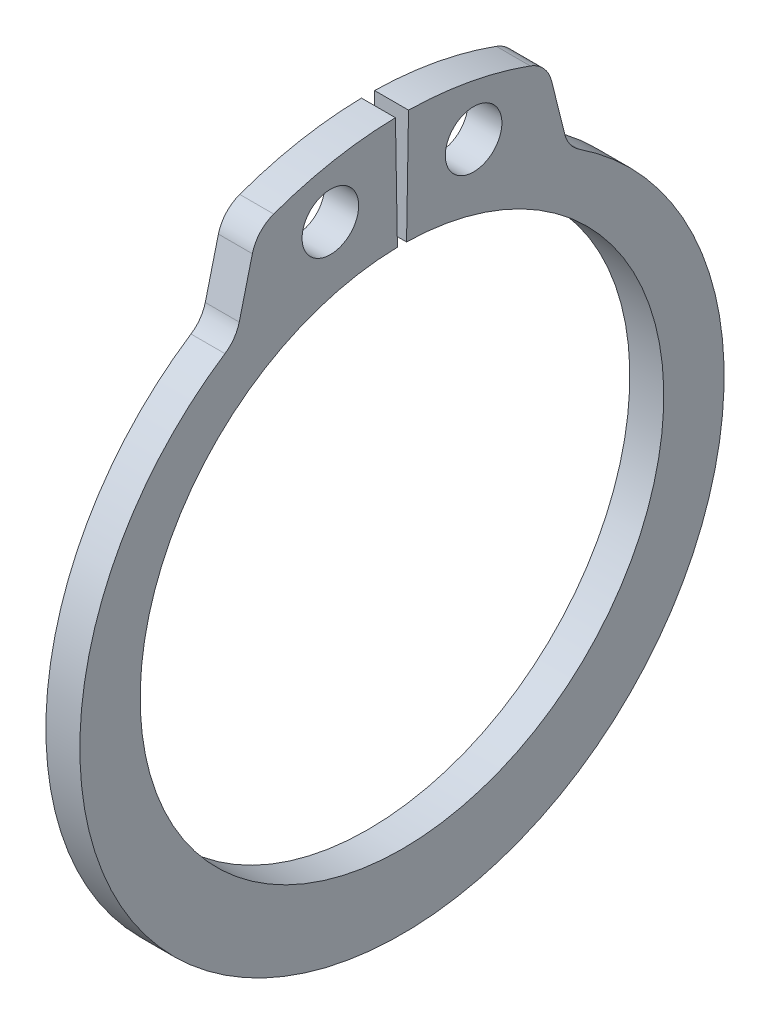
SolidWorks part; units mm, degrees
material "Cast Carbon Steel"
ref_plane "Front" through (0, 0, 0) normal (0, 0, 1) x (1, 0, 0)
ref_plane "Top" through (0, 0, 0) normal (0, 1, 0) x (1, 0, 0)
ref_plane "Right" through (0, 0, 0) normal (1, 0, 0) x (0, 0, -1)
sketch "Sketch1" plane through (0, 0, 0) normal (1, 0, 0) x (0, 0, -1)
  line L0 (0, 0) -> (0, 9.25) construction
  line L1 (-0.1614, 9.2486) -> (-0.2312, 13.248)
  line L2 (-0.2312, 13.248) -> (-4.8989, 13.1665) construction
  line L3 (-4.8989, 13.1665) -> (-5.8665, 9.2853) construction
  line L4 (0.2312, 13.248) -> (0.1614, 9.2486)
  line L5 (0.2312, 13.248) -> (4.8989, 13.1665) construction
  line L6 (4.8989, 13.1665) -> (5.8665, 9.2853) construction
  line L7 (-5.8665, 9.2853) -> (-4.9407, 7.82) construction
  line L8 (5.8665, 9.2853) -> (4.9407, 7.82) construction
  line L9 (0, -9.25) -> (0, -11.85) construction
  line L10 (-4.8989, 13.1665) -> (-0.1614, 9.2486) construction
  line L11 (-9.25, 0) -> (9.25, 0) construction
  line L12 (0, 9.25) -> (0, 13.25) construction
  line L13 (5.1364, 12.2139) -> (5.8665, 9.2853)
  line L14 (-5.1364, 12.2139) -> (-5.8665, 9.2853)
  circle A0 centre (0, 0) radius 9.25 construction
  arc A1 (-0.1614, 9.2486) -> (0.1614, 9.2486) centre (0, 0) ccw
  circle A2 centre (0, -0.4681) radius 11.3819 construction
  circle A4 centre (-2.5301, 11.2075) radius 1
  circle A5 centre (2.5301, 11.2075) radius 1
  arc A6 (-5.8665, 9.2853) -> (5.8665, 9.2853) centre (0, -0.4681) ccw
  arc A7 (0.2312, 13.248) -> (5.1364, 12.2139) centre (0, 0) cw
  arc A8 (-0.2312, 13.248) -> (-5.1364, 12.2139) centre (0, 0) ccw
  dimension "A" = 18.5
  dimension "Hole" = 2
  dimension "Smin" = 1.7333
  dimension "D1" = 75
  dimension "Angle" = 1
  dimension "H" = 4
extrude "Extrude1" add sketch "Sketch1" along normal mid plane 1.2
fillet "Fillet1" radius 1.2 4 edges at (0, 9.2853, 5.8665) (0, 12.2139, 5.1364) (0, 12.2139, -5.1364) (0, 9.2853, -5.8665)
sketch "Sketch2" plane through (0, 0, 0) normal (0, 0, 1) x (1, 0, 0)
  line L0 (-3.25, 0) -> (9.75, 0)
  line L1 (9.75, 0) -> (9.75, -10)
  line L2 (-3.25, 0) -> (-3.25, -9.5)
  line L3 (9.75, -10) -> (0.65, -10)
  line L4 (0.65, -10) -> (0.65, -9.5)
  line L5 (0.65, -9.5) -> (-0.65, -9.5)
  line L6 (-0.65, -9.5) -> (-0.65, -10)
  line L7 (-0.65, -10) -> (-3.25, -10) construction
  line L8 (-3.25, -10) -> (-3.25, 0) construction
  line L9 (0, -9.5) -> (0, 0) construction
  line L10 (9.75, 0) -> (14.0551, 0) construction
  line L11 (-3.25, -9.5) -> (-2.75, -10)
  line L12 (-2.75, -10) -> (-0.65, -10)
  dimension "D2" = 13
  dimension "D3" = 3.25
  dimension "D1" = 45
revolve "Revolve1" [suppressed] add sketch "Sketch2" angle 360 about L10
equation "\"D2@Sketch2\" = \"W@Sketch2\"*10"
equation "\"D3@Sketch2\" = \"D2@Sketch2\"/4"
equation "\"Smin@Sketch1\" = \"Smax@Sketch1\"/1.5"
equation "\"D1@Fillet1\" = \"D1@Extrude1\""
